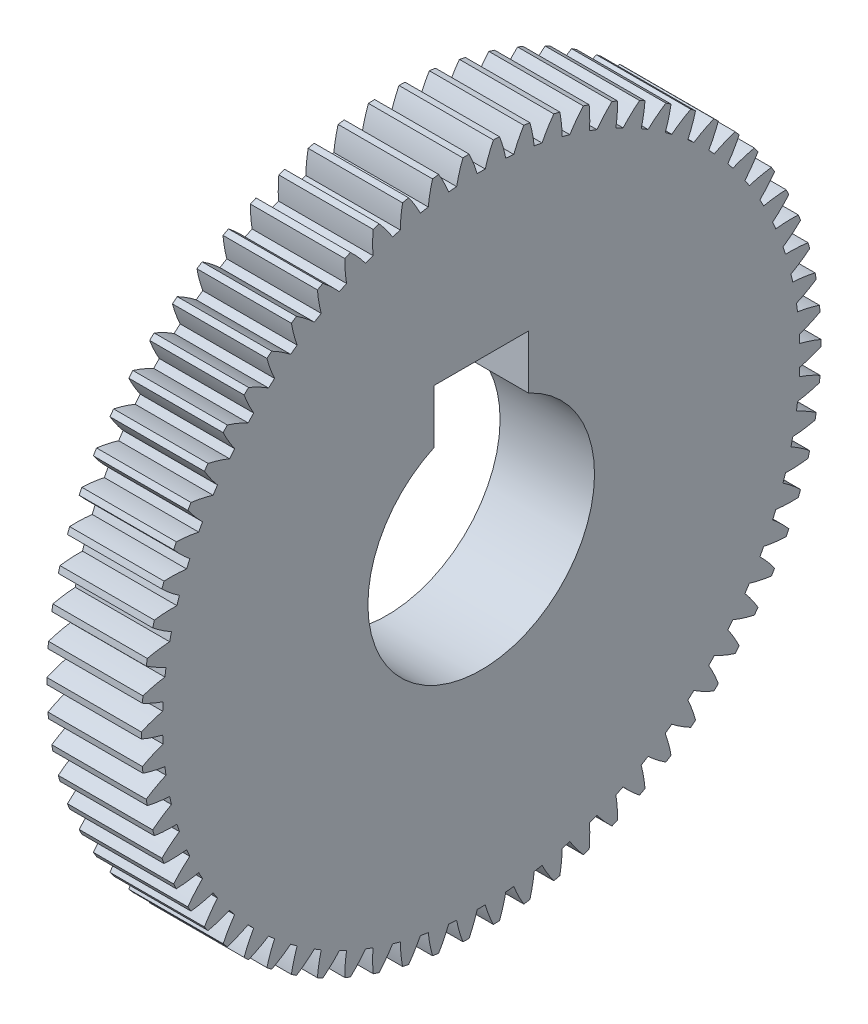
SolidWorks part; units mm, degrees
ref_plane "Plane1" through (0, 0, 0) normal (0, 0, 1) x (1, 0, 0)
ref_plane "Plane2" through (0, 0, 0) normal (0, 1, 0) x (1, 0, 0)
ref_plane "Plane3" through (0, 0, 0) normal (1, 0, 0) x (0, 0, -1)
other "Configuration Table"
sketch "HoldingSke" plane through (0, 0, 0) normal (0, 1, 0) x (1, 0, 0)
  line L0 (0, 0) -> (0.684, -1.8794)
  line L1 (-15, 0) -> (100, 0) construction
  line L2 (0, 0) -> (-2.1039, 2.3779)
  line L3 (0, 0) -> (-11.863, 4.5341)
  line L4 (0, 0) -> (2.9537, 8.1152)
  line L5 (0, 0) -> (-46.8476, -17.4728)
  line L6 (0, 0) -> (-4.1448, -2.7965)
  line L7 (-2.1039, 2.3779) -> (8.6586, 51.2059)
  line L8 (-76.2, 54.61) -> (-73.9, 54.61)
  line L9 (-71.009, 38.7566) -> (-53.1078, 45.2721)
  line L10 (-76.2, 71.12) -> (104.1128, 71.12)
  line L11 (0, 0) -> (-5, 0)
  line L12 (-76.2, 101.6) -> (-76.181, 101.6)
  line L13 (24.9733, 27.94) -> (52.9518, 28.4284)
  line L14 (24.9733, 27.94) -> (24.9743, 27.94)
  line L15 (24.9733, 27.94) -> (100.4006, 29.5858)
  line L16 (-63.627, -0.5) -> (-12.827, -0.5)
  circle A0 centre (0, 0) radius 6
  circle A1 centre (0, 0) radius 16.874
  circle A2 centre (0, 0) radius 37.5
  circle A3 centre (0, 0) radius 6
  dimension "MHD" = 33.748
  dimension "Hub_dia" = 75
  dimension "Bore" = 12
  dimension "MBD" = 12
  dimension "Num_teeth" = 70
  dimension "Pitch" = 2
  dimension "Overall_len" = 50
  dimension "Show_teeth" = 70
  dimension "Thickness" = 5
  dimension "OAL" = 50.0001
  dimension "T_dim" = 2.3
  dimension "Ap" = 20
  dimension "H" = 19.05
  dimension "Pitch_radius" = 180.3128
  dimension "Width" = 5
  dimension "Backlash" = 0.019
  dimension "Addendum_fac" = 1
  dimension "Dedendum_fac" = 1.25
  dimension "Clearance_fac" = 0.25
  dimension "Dedendum_add" = 0.001
  dimension "Module" = 0.5
sketch "BasProSke" plane through (0, 0, 0) normal (0, 1, 0) x (1, 0, 0)
  line L0 (-10, 0) -> (60, 0) construction
  line L1 (0, 0) -> (0, 18)
  line L2 (0, 0) -> (5, 0)
  line L3 (5, 0) -> (5, 18)
  line L4 (5, 18) -> (0, 18)
  dimension "Thickness" = 5
  dimension "Diameter" = 36
revolve "Base-Revolve" add sketch "BasProSke" angle 360 about L0
sketch "TooCutSke" plane through (0, 0, 0) normal (1, 0, 0) x (0, 0, -1)
  line L1 (0, 0) -> (0, 107) construction
  line L2 (0, 0) -> (-0.4259, 17.4948) construction
  line L3 (0, 0) -> (-1.5699, 34.9574) construction
  line L4 (-0.4259, 17.4948) -> (-0.785, 17.4787) construction
  arc A0 (0.2122, 16.8727) -> (-0.2122, 16.8727) centre (0, 0) ccw
  arc A1 (0.6565, 18.0134) -> (-0.6565, 18.0134) centre (0, 0) ccw
  circle A2 centre (0, 0) radius 17.5 construction
  circle A3 centre (0, 0) radius 16.4446 construction
  arc A4 (-0.2122, 16.8727) -> (-0.6565, 18.0134) centre (-6.9321, 14.9121) ccw
  arc A5 (0.6565, 18.0134) -> (0.2122, 16.8727) centre (6.9321, 14.9121) ccw
  dimension "Root_dia" = 33.748
  dimension "Overcut_dia" = 36.0508
  dimension "Pitch_dia" = 35
  dimension "Base_dia" = 32.8892
  dimension "Flank_rad" = 7
  dimension "Half_ang" = 2.571
  dimension "Half_CT" = 0.3594
extrude "ToothCut" cut sketch "TooCutSke" along normal through all
fillet "Breaks" [suppressed] radius 0.01
fillet "RootFillets" [suppressed] radius 0.126
pattern_circular "TeethCuts" count 70 every 5.143 about axis through (-10, 0, 0) along (1, 0, 0) of "ToothCut", "RootFillets", "Breaks"
sketch "HubNeaOneSke" plane through (0, 0, 0) normal (-1, 0, 0) x (0, 0, 1)
  circle A0 centre (0, 0) radius 16.874
  dimension "Diameter" = 33.748
extrude "HubNearOne" [suppressed] add sketch "HubNeaOneSke" along normal blind 45.0001
sketch "HubNeaBotSke" plane through (0, 0, 0) normal (-1, 0, 0) x (0, 0, 1)
  circle A0 centre (0, 0) radius 16.874
  dimension "Diameter" = 33.748
extrude "HubNearBoth" [suppressed] add sketch "HubNeaBotSke" along normal blind 22.5
ref_plane "FarPln" through (5, 0, 0) normal (1, 0, 0) x (0, 0, -1)
sketch "HubFarSke" plane through (5, 0, 0) normal (1, 0, 0) x (0, 0, -1)
  circle A0 centre (0, 0) radius 16.874
  dimension "Diameter" = 33.748
extrude "HubFar" [suppressed] add sketch "HubFarSke" along normal blind 22.5
sketch "BorSke" plane through (0, 0, 0) normal (1, 0, 0) x (0, 0, -1)
  circle A0 centre (0, 0) radius 6
  dimension "Diameter" = 12
extrude "Bore" cut sketch "BorSke" along normal mid plane 100.0001
sketch "KeySke" plane through (0, 0, 0) normal (1, 0, 0) x (0, 0, -1)
  line L0 (-2.5, 0) -> (-2.5, 8.3)
  line L1 (-2.5, 8.3) -> (2.5, 8.3)
  line L2 (2.5, 8.3) -> (2.5, 0)
  line L3 (0, 0) -> (0, 34) construction
  line L4 (-2.5, 0) -> (2.5, 0)
  dimension "Width" = 5
  dimension "Offset" = 8.3
extrude "Keyway" cut sketch "KeySke" along normal mid plane 100.0001
pattern_circular "Keyway2" [suppressed] count 2 every 90 about axis through (-10, 0, 0) along (1, 0, 0)
equation "' \"Module@HoldingSke\" = 6.35"
equation "' \"Num_teeth@HoldingSke\" = 12"
equation "' \"Ap@HoldingSke\" =  20"
equation "' \"Ap@HoldingSke\" = 20"
equation "' \"Width@HoldingSke\" = 0.5 * 25.4"
equation "' \"Hub_dia@HoldingSke\"= 1 * 25.4"
equation "' \"Hub_dia@HoldingSke\" = 1 * 25.4"
equation "' \"Overall_len@HoldingSke\" = 1.0 * 25.4"
equation "' \"Bore@HoldingSke\" = 0.75 * 25.4"
equation "' \"T_dim@HoldingSke\" = 0.1 * 25.4"
equation "' \"Width@KeySke\" = 0.25 * 25.4"
equation "' \"Show_teeth@HoldingSke\" = 13"
equation "' \"Backlash@HoldingSke\" = 0.009 * 25.4"
equation "' \"Addendum_fac@HoldingSke\" = 1.0"
equation "' \"Dedendum_fac@HoldingSke\" = 1.25"
equation "' \"Dedendum_add@HoldingSke\" = 0.00005 * 25.4"
equation "' \"Clearance_fac@HoldingSke\" = 0.25"
equation "\"Pitch@HoldingSke\" = 1 / \"Module@HoldingSke\""
equation "\"Overcut_dia@TooCutSke\" = (\"Num_teeth@HoldingSke\" + 2 * \"Addendum_fac@HoldingSke\") / \"Pitch@HoldingSke\" + 0.002 * 25.4"
equation "\"Pitch_dia@TooCutSke\" = \"Num_teeth@HoldingSke\" / \"Pitch@HoldingSke\""
equation "\"Base_dia@TooCutSke\" = \"Num_teeth@HoldingSke\" / \"Pitch@HoldingSke\" * cos((\"Ap@HoldingSke\"  * 3.14159265 / 180))"
equation "\"Root_dia@TooCutSke\" = (\"Num_teeth@HoldingSke\" + 2) / \"Pitch@HoldingSke\" - 2 * (\"Addendum_fac@HoldingSke\" + \"Dedendum_fac@HoldingSke\") / \"Pitch@HoldingSke\" - \"Dedendum_add@HoldingSke\" * 2"
equation "\"Half_ang@TooCutSke\" = 180 / \"Num_teeth@HoldingSke\""
equation "\"Half_CT@TooCutSke\" = \"Num_teeth@HoldingSke\" / \"Pitch@HoldingSke\" * sin((3.14159265 / 2 / \"Num_teeth@HoldingSke\")) / 2 - 7 * \"Backlash@HoldingSke\" / 4"
equation "\"Flank_rad@TooCutSke\" = \"Num_teeth@HoldingSke\" / \"Pitch@HoldingSke\" / 5"
equation "\"Radius@RootFillets\" = \"Clearance_fac@HoldingSke\" / \"Pitch@HoldingSke\" + \"Dedendum_add@HoldingSke\""
equation "\"Break_rad@Breaks\" = 0.02 / \"Pitch@HoldingSke\""
equation "\"Thickness@HoldingSke\" = \"Width@HoldingSke\""
equation "\"OAL@HoldingSke\" = \"Thickness@HoldingSke\""
equation "\"MHD@HoldingSke\" = (\"Num_teeth@HoldingSke\" + 2) / \"Pitch@HoldingSke\" - 2 * (\"Addendum_fac@HoldingSke\" + \"Dedendum_fac@HoldingSke\")  / \"Pitch@HoldingSke\" - \"Dedendum_add@HoldingSke\" * 2"
equation "\"MBD@HoldingSke\" = (\"Num_teeth@HoldingSke\" + 2) / \"Pitch@HoldingSke\" - 2 * (\"Addendum_fac@HoldingSke\" + \"Dedendum_fac@HoldingSke\")  / \"Pitch@HoldingSke\" - \"Dedendum_add@HoldingSke\" * 2 - 0.002 * 25.4"
equation "\"MHD@HoldingSke\" = ((sgn( \"MHD@HoldingSke\" - \"Hub_dia@HoldingSke\" )-1)*( \"MHD@HoldingSke\" - \"Hub_dia@HoldingSke\" ))/-2+ \"Hub_dia@HoldingSke\""
equation "\"MBD@HoldingSke\" = ((sgn( \"MBD@HoldingSke\" - \"Bore@HoldingSke\" )-1)*( \"MBD@HoldingSke\" - \"Bore@HoldingSke\" ))/-2+ \"Bore@HoldingSke\""
equation "\"OAL@HoldingSke\" = ((sgn( \"OAL@HoldingSke\" - \"Overall_len@HoldingSke\" )+1)*( \"OAL@HoldingSke\" - \"Overall_len@HoldingSke\" ))/2 + \"Overall_len@HoldingSke\" + 0.000002 * 25.4"
equation "\"Num_teeth@TeethCuts\" = int( \"Show_teeth@HoldingSke\" ) + 1"
equation "\"Num_teeth@TeethCuts\" = ((sgn( \"Num_teeth@TeethCuts\" - \"Num_teeth@HoldingSke\" )-1)*( \"Num_teeth@TeethCuts\" - \"Num_teeth@HoldingSke\" ))/-2+ \"Num_teeth@HoldingSke\""
equation "\"Num_teeth@TeethCuts\" = ((sgn( \"Num_teeth@TeethCuts\" - 2.0)+1)*( \"Num_teeth@TeethCuts\" - 2.0))/2 +2.0"
equation "\"Angle@TeethCuts\" = 360.0 / \"Num_teeth@HoldingSke\""
equation "\"Diameter@BasProSke\" = (\"Num_teeth@HoldingSke\" + 2 * \"Addendum_fac@HoldingSke\") / \"Pitch@HoldingSke\""
equation "\"Thickness@BasProSke\"  = \"Thickness@HoldingSke\""
equation "' \"Fillet_rad@BasProSke\" =  \"Thickness@HoldingSke\" * 0.05"
equation "' \"Fillet_rad@BasProSke\" = \"Thickness@HoldingSke\" * 0.05"
equation "\"MHD@HoldingSke\" = ((sgn( \"MHD@HoldingSke\" - \"Root_dia@TooCutSke\" )-1)*( \"MHD@HoldingSke\" - \"Root_dia@TooCutSke\" ))/-2+ \"Root_dia@TooCutSke\""
equation "\"Diameter@HubNeaOneSke\" = \"MHD@HoldingSke\""
equation "\"Length@HubNearOne\" = \"OAL@HoldingSke\" - \"Thickness@BasProSke\""
equation "\"Diameter@HubNeaBotSke\" = \"MHD@HoldingSke\""
equation "\"Length@HubNearBoth\" = ( \"OAL@HoldingSke\" - \"Thickness@BasProSke\" ) / 2.0"
equation "\"Thickness@FarPln\" = \"Thickness@BasProSke\""
equation "\"Diameter@HubFarSke\" = \"MHD@HoldingSke\""
equation "\"Length@HubFar\" = ( \"OAL@HoldingSke\" - \"Thickness@BasProSke\" ) / 2.0"
equation "\"Diameter@BorSke\" = \"MBD@HoldingSke\""
equation "\"D1@Bore\" = \"OAL@HoldingSke\" * 2.0"
equation "\"D1@Keyway\" = \"OAL@HoldingSke\" * 2.0"
equation "\"Offset@KeySke\" = \"T_dim@HoldingSke\" + \"MBD@HoldingSke\" / 2.0"
